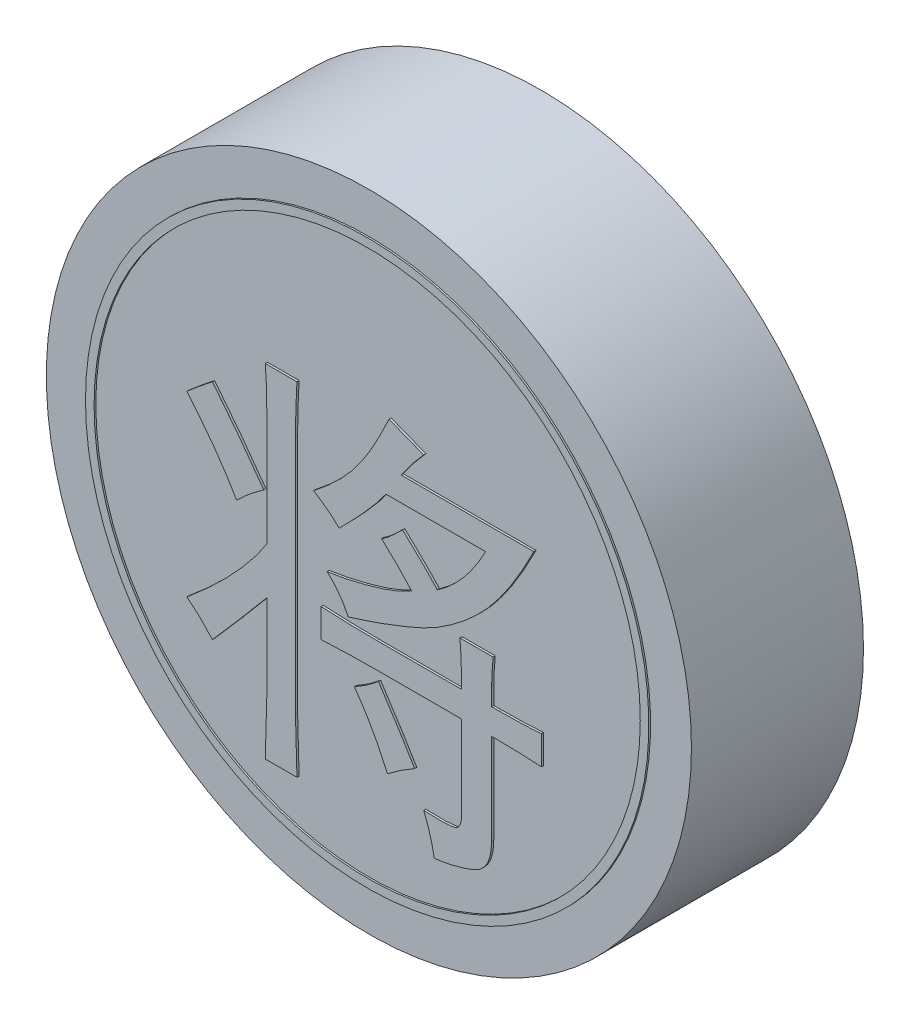
SolidWorks part; units mm, degrees
ref_plane "前视基准面" through (0, 0, 0) normal (0, 0, 1) x (1, 0, 0)
ref_plane "上视基准面" through (0, 0, 0) normal (0, 1, 0) x (1, 0, 0)
ref_plane "右视基准面" through (0, 0, 0) normal (1, 0, 0) x (0, 0, -1)
other "Configuration Table"
sketch "草图1" plane through (0, 0, 0) normal (0, 0, 1) x (1, 0, 0)
  circle A0 centre (0, 0) radius 15
  dimension "D1" = 30
extrude "Diameter30_Height8" add sketch "草图1" against normal blind 8
sketch "草图2" plane through (0, 0, 0) normal (0, 0, 1) x (1, 0, 0)
  text T0 "将" font "SimHei" height 12
extrude "Character_将" add sketch "草图2" along normal blind 0.1
sketch "草图3" plane through (0, 0, 0) normal (0, 0, 1) x (1, 0, 0)
  circle A0 centre (0, 0) radius 13.1
  circle A1 centre (0, 0) radius 12.7
extrude "Ink_ring" add sketch "草图3" along normal blind 0.08
